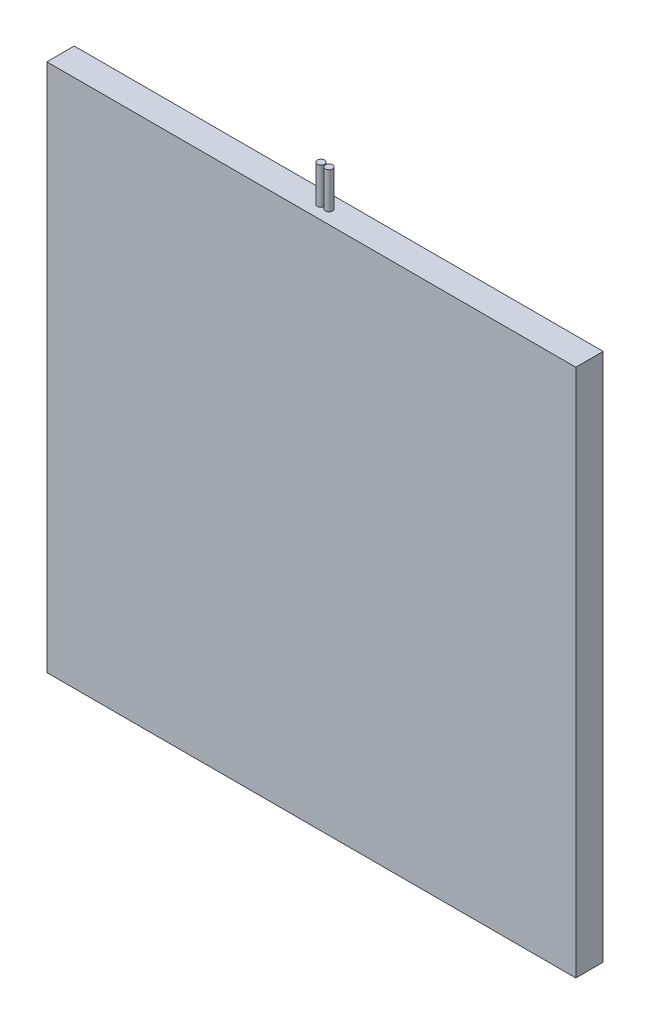
SolidWorks part; units mm, degrees
ref_plane "Plan de face" through (0, 0, 0) normal (0, 0, 1) x (1, 0, 0)
ref_plane "Plan de dessus" through (0, 0, 0) normal (0, 1, 0) x (1, 0, 0)
ref_plane "Plan de droite" through (0, 0, 0) normal (1, 0, 0) x (0, 0, -1)
sketch "Esquisse1" plane through (0, 0, 0) normal (0, 0, 1) x (1, 0, 0)
  line L1 (-72.5, 72.5) -> (72.5, 72.5)
  line L2 (-72.5, 72.5) -> (-72.5, -72.5)
  line L3 (-72.5, -72.5) -> (72.5, -72.5)
  line L4 (72.5, 72.5) -> (72.5, -72.5)
  line L5 (-72.5, 72.5) -> (72.5, -72.5) construction
  line L6 (-72.5, -72.5) -> (72.5, 72.5) construction
  point P0 (0, 0)
  dimension "D1" = 145
  dimension "D2" = 145
extrude "Boss.-Extru.1" add sketch "Esquisse1" along normal blind 5
sketch "Esquisse2" plane through (0, 0, 0) normal (0, 0, -1) x (-1, 0, 0)
  line L0 (-72.5, 43.5) -> (72.5, 43.5)
  line L1 (-72.5, 46) -> (72.5, 46)
  line L2 (-43.5, 72.5) -> (-43.5, -72.5)
  line L3 (-46, 72.5) -> (-46, -72.5)
  line L4 (-72.5, 72.5) -> (-72.5, -72.5)
  line L5 (-72.5, -72.5) -> (72.5, -72.5)
  line L6 (72.5, -72.5) -> (72.5, 72.5)
  line L7 (72.5, 72.5) -> (-72.5, 72.5)
  line L8 (-72.5, 46) -> (-72.5, 43.5)
  line L9 (-46, -72.5) -> (-43.5, -72.5)
  line L10 (72.5, -48) -> (72.5, -45.5)
  line L11 (43.5, 72.5) -> (41, 72.5)
  line L12 (-72.5, 13) -> (72.5, 13)
  line L13 (-72.5, 15.5) -> (72.5, 15.5)
  line L14 (-72.5, -17.5) -> (72.5, -17.5)
  line L15 (-72.5, -15) -> (72.5, -15)
  line L16 (-72.5, -48) -> (41, -48)
  line L17 (-72.5, -45.5) -> (41, -45.5)
  line L18 (-17, 72.5) -> (-17, -72.5)
  line L19 (-14.5, 72.5) -> (-14.5, -72.5)
  line L20 (12, 72.5) -> (12, -72.5)
  line L21 (14.5, 72.5) -> (14.5, -72.5)
  line L22 (41, 72.5) -> (41, -45.5)
  line L23 (43.5, 72.5) -> (43.5, -45.5)
  line L24 (72.5, 43.5) -> (72.5, 46)
  line L25 (72.5, 13) -> (72.5, 15.5)
  line L26 (72.5, -17.5) -> (72.5, -15)
  line L27 (41, -72.5) -> (43.5, -72.5)
  line L28 (12, -72.5) -> (14.5, -72.5)
  line L29 (-17, -72.5) -> (-14.5, -72.5)
  line L30 (-72.5, -45.5) -> (-72.5, -48)
  line L31 (-72.5, -15) -> (-72.5, -17.5)
  line L32 (-72.5, 15.5) -> (-72.5, 13)
  line L33 (14.5, 72.5) -> (12, 72.5)
  line L34 (-14.5, 72.5) -> (-17, 72.5)
  line L35 (-43.5, 72.5) -> (-46, 72.5)
  line L36 (43.5, -48) -> (43.5, -72.5)
  line L37 (43.5, -45.5) -> (72.5, -45.5)
  line L38 (41, -48) -> (41, -72.5)
  line L39 (43.5, -48) -> (72.5, -48)
  line L40 (72.5, 72.5) -> (72.5, -72.5) construction
  line M10 (72.5, -72.5) -> (72.5, 72.5)
  line M11 (72.5, 72.5) -> (-72.5, 72.5)
  dimension "D2" = 29
  dimension "D4" = 29
  dimension "D8" = 29
  dimension "D9" = 28
  dimension "D1" = 0
  dimension "D3" = 2.5
  dimension "D5" = 2.5
  dimension "D6" = 4
  dimension "D7" = 4
extrude "Boss.-Extru.2" add sketch "Esquisse2" along normal blind 2.5 contours L23 L22 L1 M11 | L23 L1 L22 L0 | L1 L23 L0 M10 | L23 L0 L22 L13 | L22 L1 L21 L0 | L21 L20 L1 M11 | L21 L1 L20 L0 | L21 L0 L20 L13 | L23 L13 L22 L12 | L13 L23 L12 M10 | L23 L12 L22 L15 | L21 L12 L20 L15 | L21 L13 L20 L12 | L20 L13 L19 L12 | L3 L1 L2 M11 | L3 L13 L2 L0
sketch "Esquisse3" plane through (0, 0, 0) normal (0, 0, -1) x (-1, 0, 0)
  line L0 (69.5, 69.5) -> (69.5, -69.5)
  line L1 (72.5, 72.5) -> (-72.5, 72.5)
  line L2 (72.5, 72.5) -> (72.5, -72.5)
  line L3 (72.5, -72.5) -> (-72.5, -72.5)
  line L4 (-72.5, 72.5) -> (-72.5, -72.5)
  line L5 (72.5, 72.5) -> (-72.5, -72.5) construction
  line L6 (72.5, -72.5) -> (-72.5, 72.5) construction
  line L7 (69.5, -69.5) -> (-69.5, -69.5)
  line L8 (-69.5, 69.5) -> (-69.5, -69.5)
  line L9 (69.5, 69.5) -> (-69.5, 69.5)
  point P0 (0, 0)
  dimension "D1" = 3
extrude "Boss.-Extru.3" add sketch "Esquisse3" along normal blind 2.5
sketch "Esquisse4" plane through (0, 72.5, 0) normal (0, 1, 0) x (1, 0, 0)
  line L0 (-72.5, -1.25) -> (72.5, -1.25) construction
  line L1 (-72.5, -5) -> (-72.5, 2.5) construction
  line L2 (72.5, -5) -> (72.5, 2.5) construction
  circle A0 centre (-1.1, -1.25) radius 1
  circle A1 centre (1.1, -1.25) radius 1
  dimension "D1" = 2
  dimension "D3" = 2
  dimension "D2" = 1.1
  dimension "D4" = 1.1
extrude "Boss.-Extru.4" add sketch "Esquisse4" along normal blind 10
